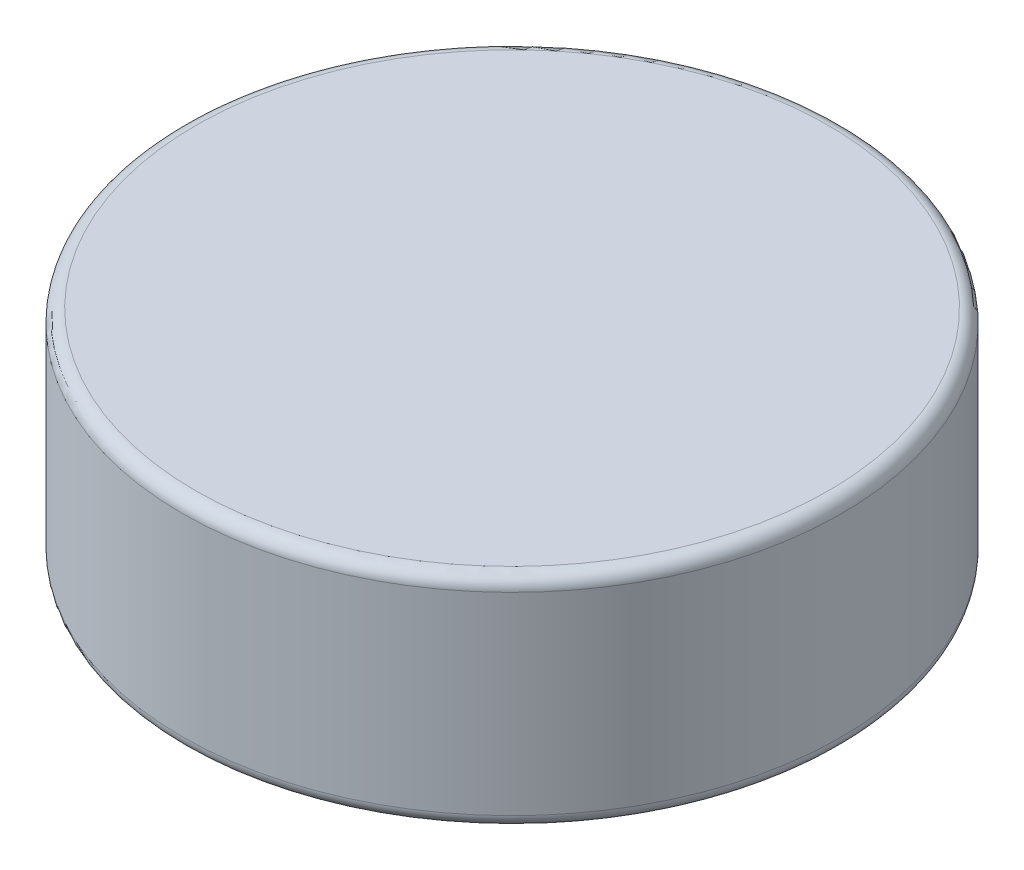
SolidWorks part; units mm, degrees
material "Carbon Fiber"
ref_plane "Front Plane" through (0, 0, 0) normal (0, 0, 1) x (1, 0, 0)
ref_plane "Top Plane" through (0, 0, 0) normal (0, 1, 0) x (1, 0, 0)
ref_plane "Right Plane" through (0, 0, 0) normal (1, 0, 0) x (0, 0, -1)
sketch "Sketch1" plane through (0, 0, 0) normal (0, 1, 0) x (1, 0, 0)
  line L2 (0, -55) -> (0, 55) construction
  circle A1 centre (0, 0) radius 75
  dimension "D1" = 150
extrude "Boss-Extrude1" add sketch "Sketch1" along normal mid plane 50
fillet "Fillet1" radius 3 2 edges at (0, 25, 75) (0, -25, 75)
